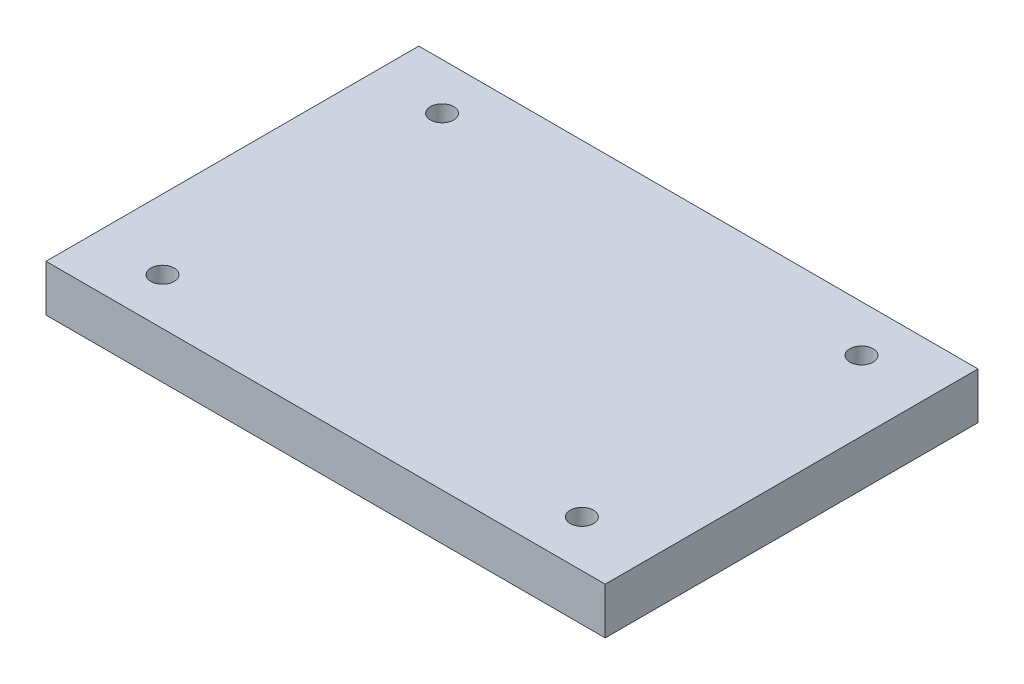
SolidWorks part; units mm, degrees
ref_plane "前视基准面" through (0, 0, 0) normal (0, 0, 1) x (1, 0, 0)
ref_plane "上视基准面" through (0, 0, 0) normal (0, 1, 0) x (1, 0, 0)
ref_plane "右视基准面" through (0, 0, 0) normal (1, 0, 0) x (0, 0, -1)
other "Configuration Table"
sketch "草图1" plane through (0, 0, 0) normal (0, 1, 0) x (1, 0, 0)
  line L1 (-120, -80) -> (120, -80)
  line L2 (-120, -80) -> (-120, 80)
  line L3 (-120, 80) -> (120, 80)
  line L4 (120, -80) -> (120, 80)
extrude "凸台-拉伸1" add sketch "草图1" against normal blind 20
sketch "草图2" plane through (0, 0, 0) normal (0, 1, 0) x (1, 0, 0)
  circle A0 centre (90, 60) radius 5
  circle A1 centre (-90, 60) radius 5
  circle A2 centre (90, -60) radius 5
  circle A3 centre (-90, -60) radius 5
extrude "切除-拉伸1" cut sketch "草图2" against normal blind 20
